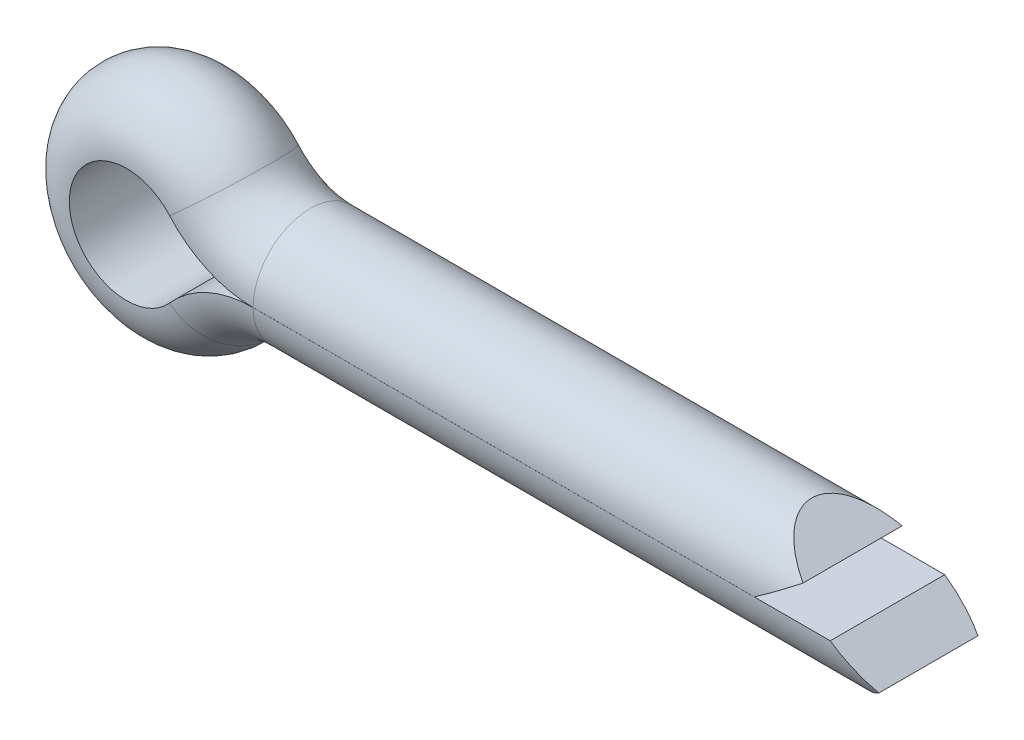
SolidWorks part; units mm, degrees
ref_plane "Front" through (0, 0, 0) normal (0, 0, 1) x (1, 0, 0)
ref_plane "Top" through (0, 0, 0) normal (0, 1, 0) x (1, 0, 0)
ref_plane "Right" through (0, 0, 0) normal (1, 0, 0) x (0, 0, -1)
sketch "PathSke" plane through (0, 0, 0) normal (0, 0, 1) x (1, 0, 0)
  line L0 (45, 4.75) -> (0, 4.75)
  line L1 (0, -4.75) -> (51.3, -4.75)
  line L2 (0, 0) -> (49.7718, 0) construction
  line L3 (0, 0) -> (0, 16.5256) construction
  line L4 (-20, 0) -> (-20, 14.2137) construction
  arc A0 (0, 4.75) -> (-3.3649, 6.2722) centre (0, 9.2303) cw
  arc A1 (-3.3649, 6.2722) -> (-3.3649, -6.2722) centre (-10.5, 0) ccw
  arc A2 (-3.3649, -6.2722) -> (0, -4.75) centre (0, -9.2303) cw
  dimension "Diameter" = 9.5
  dimension "Head_dia" = 19
  dimension "Head_ht" = 20
  dimension "Length" = 45
  dimension "Tip_offset" = 6.3
ref_plane "SectionPlane" through (45, 0, 0) normal (1, 0, 0) x (0, 0, -1)
sketch "SectionSke" plane through (45, 0, 0) normal (1, 0, 0) x (0, 0, -1)
  line L1 (-4.75, 0.002) -> (4.75, 0.002)
  arc A0 (4.75, 0.002) -> (-4.75, 0.002) centre (0, 0) ccw
  dimension "Diameter" = 9.5
  dimension "D1" = 0.002
sweep "Body" add profiles "SectionSke" path "PathSke"
sketch "ConeCutSke" plane through (0, 0, 0) normal (0, 0, 1) x (1, 0, 0)
  line L0 (0, 0) -> (0, 16.2682) construction
  line L1 (0, 0) -> (75.9079, 0) construction
  line L2 (0, 0) -> (51.3, 0) construction
  line L3 (45, 2.376) -> (41.6038, 4.76)
  line L4 (45, 0.002) -> (45, 4.75) construction
  line L6 (45, 2.376) -> (41.5982, 0)
  line L7 (51.3, -2.376) -> (47.8982, 0)
  line L8 (51.3, -4.75) -> (51.3, -0.002) construction
  line L9 (51.3, -2.376) -> (47.9038, -4.76)
  line L10 (47.8982, 0) -> (41.5982, 0)
  line L11 (41.6038, 4.76) -> (51.31, 4.76)
  line L12 (51.31, 4.76) -> (51.31, -4.76)
  line L13 (51.31, -4.76) -> (47.9038, -4.76)
  line L14 (45, 4.75) -> (0, 4.75) construction
  dimension "D1" = 0.01
  dimension "D2" = 0.01
  dimension "D3" = 70
  dimension "D4" = 70
extrude "ConeCut" cut sketch "ConeCutSke" against normal through all and the other way through all
equation "' \"Diameter@PathSke\" = 9.5"
equation "' \"Head_dia@PathSke\" = 19"
equation "' \"Head_ht@PathSke\" = 20"
equation "' \"Tip_offset@PathSke\" = 6.3"
equation "' \"Length@PathSke\" = 45"
equation "' \"Diameter@PathSke\" = 1"
equation "' \"Head_dia@PathSke\" = 2"
equation "' \"Head_ht@PathSke\" = 3"
equation "' \"Tip_offset@PathSke\" = 2.5"
equation "' \"Length@PathSke\" = 8"
equation "' \"Diameter@PathSke\" = 0.5"
equation "' \"Head_dia@PathSke\" = 1"
equation "' \"Head_ht@PathSke\" = 2"
equation "' \"Tip_offset@PathSke\" = 1.6"
equation "' \"Length@PathSke\" = 4"
equation "\"Diameter@SectionSke\" = \"Diameter@PathSke\""
equation "\"Length@SectionPlane\" = \"Length@PathSke\""
